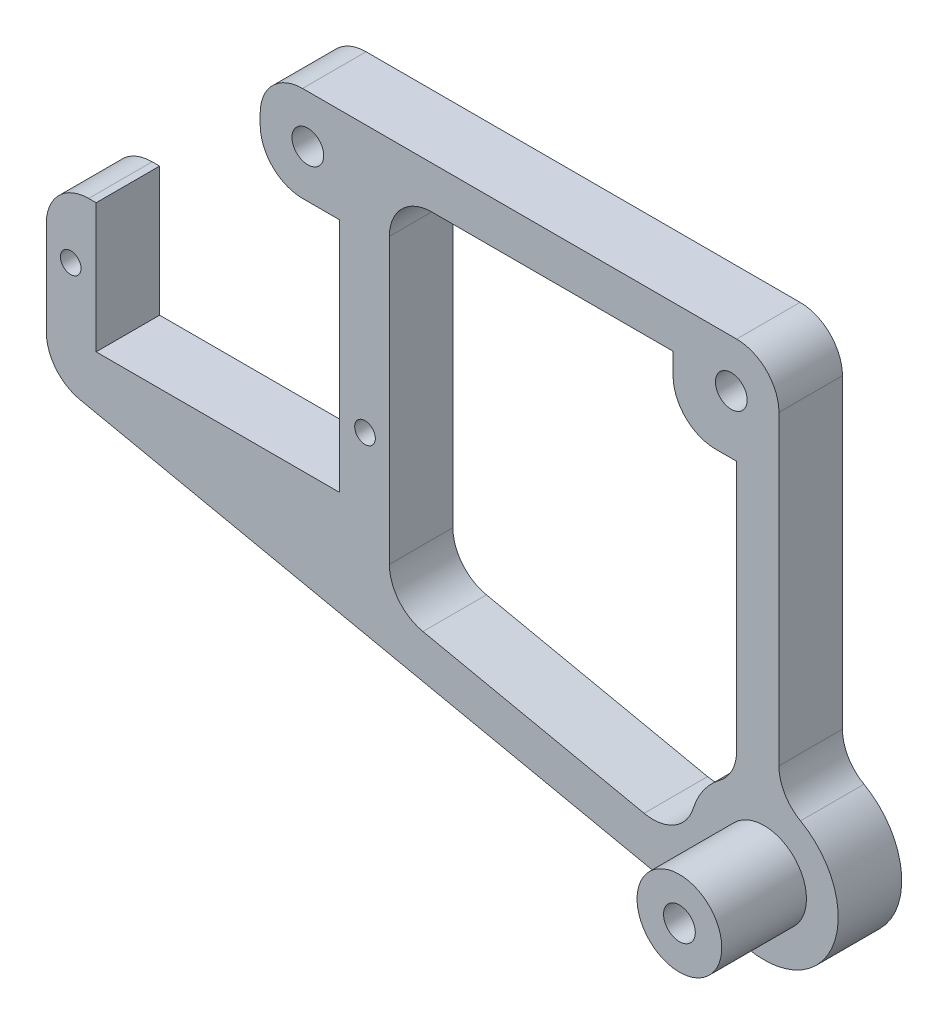
SolidWorks part; units mm, degrees
ref_plane "Front Plane" through (0, 0, 0) normal (0, 0, 1) x (1, 0, 0)
ref_plane "Top Plane" through (0, 0, 0) normal (0, 1, 0) x (1, 0, 0)
ref_plane "Right Plane" through (0, 0, 0) normal (1, 0, 0) x (0, 0, -1)
sketch "screw holes" plane through (0, 0, 0) normal (0, 0, 1) x (1, 0, 0)
  line L0 (-20, 0) -> (20, 0) construction
  circle A0 centre (-20, 0) radius 1.5
  circle A1 centre (20, 0) radius 1.5
  point P4 (0, 0)
  dimension "D1" = 3
  dimension "D2" = 40
sketch "bearings" plane through (0, 0, 0) normal (0, 0, 1) x (1, 0, 0)
  line L1 (-8, -16.5) -> (8, -16.5)
  line L2 (-8, -16.5) -> (-8, -7.5)
  line L3 (-8, -7.5) -> (8, -7.5)
  line L4 (8, -16.5) -> (8, -7.5)
  point P4 (0, -7.5)
  dimension "D1" = 7.5
  dimension "D2" = 16
  dimension "D3" = 9
sketch "bottom rod mount" plane through (0, 0, 0) normal (0, 0, 1) x (1, 0, 0)
  line L0 (-20, 0) -> (-20, -14.6) construction
  line L1 (-40, -14.6) -> (40, -14.6)
  point P6 (0, -14.6)
  dimension "D1" = 80
  dimension "D2" = 14.6
sketch "servo body" plane through (0, 0, 0) normal (0, 0, 1) x (1, 0, 0)
  line L1 (-40, -14.6) -> (-17, -14.6)
  line L2 (-40, -14.6) -> (-40, -26.8)
  line L3 (-40, -26.8) -> (-17, -26.8)
  line L4 (-17, -14.6) -> (-17, -26.8)
  line L5 (-44.7, -26.8) -> (-12.3, -26.8)
  line L6 (-44.7, -26.8) -> (-44.7, -14.6)
  line L7 (-44.7, -14.6) -> (-12.3, -14.6)
  line L8 (-12.3, -26.8) -> (-12.3, -14.6)
  point P9 (-28.5, -14.6)
  point P10 (-28.5, -14.6)
  dimension "D1" = 12.2
  dimension "D2" = 23
  dimension "D3" = 32.4
sketch "servo screw holes" plane through (0, 0, 0) normal (0, 0, 1) x (1, 0, 0)
  line L0 (-41.425, -20.7) -> (-15.575, -20.7) construction
  line L1 (-40, -26.8) -> (-17, -26.8) construction
  line L2 (-44.7, -26.8) -> (-44.7, -14.6) construction
  circle A0 centre (-42.4, -20.7) radius 0.975
  circle A1 centre (-14.6, -20.7) radius 0.975
  point P7 (-28.5, -26.8)
  point P10 (-44.7, -20.7)
  point P17 (-28.5, -20.7)
  dimension "D1" = 1.95
  dimension "D2" = 25.85
sketch "servo motor center" plane through (0, 0, 0) normal (0, 0, 1) x (1, 0, 0)
  line L0 (-40, -14.6) -> (40, -14.6) construction
  line L1 (-40, -26.8) -> (-17, -26.8) construction
  line L2 (-17, -14.6) -> (-17, -26.8) construction
  circle A0 centre (-23.1, -20.7) radius 6.1 construction
  point P9 (-23.1, -20.7)
sketch "pen pivot line" plane through (0, 0, 0) normal (0, 0, 1) x (1, 0, 0)
  line L0 (20, 0) -> (20, -38) construction
  line L1 (-34.4923, -38) -> (49965.5077, -38) construction
  dimension "D1" = 38
sketch "pen pivot point" plane through (0, 0, 0) normal (0, 0, 1) x (1, 0, 0)
  line L1 (-200034.4923, -38) -> (249965.5077, -38) construction
  circle A0 centre (23.1, -38) radius 4.6033 construction
  point P1 (-23.1, -20.7)
  point P2 (-20, 0)
  point P3 (23.1, -38)
  dimension "D1" = 3.1
  dimension "D2" = 3.1
sketch "center distance" plane through (0, 0, 0) normal (0, 0, 1) x (1, 0, 0)
  line L0 (23.1, -38) -> (-23.1, -20.7) construction
  dimension "D1" = 49.3328
sketch "body" plane through (0, 0, 0) normal (0, 0, 1) x (1, 0, 0)
  line L0 (-24.5, 4.5) -> (24.5, 4.5)
  line L6 (-24.5, -4.5) -> (-24.5, 4.5)
  line L9 (24.5, 4.5) -> (24.5, -31.1414)
  line L11 (-44.7, -14.6) -> (-40, -14.6)
  line L12 (-40, -14.6) -> (-40, -26.8)
  line L13 (-40, -26.8) -> (-17, -26.8)
  line L14 (-17, -26.8) -> (-17, -4.5)
  line L16 (-17, -4.5) -> (-24.5, -4.5)
  line L18 (-12.3, 0.5) -> (14.5, 0.5)
  line L19 (14.5, 0.5) -> (14.5, -5.5)
  line L20 (16.2912, -39.6249) -> (-12.3, -33.5713)
  line L21 (-12.3, -26.8) -> (-12.3, -14.6) construction
  line L22 (-12.3, -33.5713) -> (-12.3, 0.5)
  line L25 (14.5, -5.5) -> (20.5, -5.5)
  line L26 (20.5, -5.5) -> (20.5, -31.5008)
  line L27 (-44.7, -30.8) -> (21.65, -44.8482)
  line L28 (-44.7, -14.6) -> (-44.7, -30.8)
  circle A0 centre (-20, 0) radius 1.5 construction
  circle A1 centre (-20, 0) radius 1.5 construction
  arc A4 (20.5, -31.5008) -> (16.2912, -39.6249) centre (23.1, -38) ccw
  arc A5 (21.65, -44.8482) -> (24.5, -31.1414) centre (23.1, -38) ccw
  point P1 (-21.5, 0)
  point P16 (-20, 1.5)
  dimension "D1" = 3
  dimension "D7" = 14
  dimension "D2" = 3
  dimension "D3" = 4.5
  dimension "D5" = 4
  dimension "D6" = 4
  dimension "D8" = 4.5
  dimension "D10" = 4
  dimension "D11" = 5.5
  dimension "D12" = 5.5
  dimension "D13" = 4
extrude "Boss-Extrude1" add sketch "body" along normal blind 6
sketch "Sketch12" plane through (0, 0, 0) normal (0, 0, 1) x (1, 0, 0)
  circle A1 centre (20, 0) radius 1.5
  circle A2 centre (20, 0) radius 1.5
  circle A3 centre (-20, 0) radius 1.5
  circle A4 centre (-20, 0) radius 1.5
  dimension "D1" = 0
  dimension "D2" = 0
extrude "mount screw holes" cut sketch "Sketch12" along normal up to next
sketch "Sketch13" plane through (0, 0, 0) normal (0, 0, 1) x (1, 0, 0)
  circle A0 centre (23.1, -38) radius 4
  dimension "D1" = 8
extrude "gear shaft" add sketch "Sketch13" along normal blind 8 from surface at 6 starting at face at (21.5, 0, 6)
sketch "Sketch14" plane through (0, 0, 0) normal (0, 0, 1) x (1, 0, 0)
  circle A0 centre (23.1, -38) radius 1.5
  dimension "D1" = 3
extrude "gear screw hole" cut sketch "Sketch14" along normal through all
sketch "Sketch15" plane through (0, 0, 0) normal (0, 0, 1) x (1, 0, 0)
  circle A0 centre (-14.6, -20.7) radius 0.975 construction
  circle A1 centre (-42.4, -20.7) radius 0.975 construction
  circle A2 centre (-14.6, -20.7) radius 0.975
  circle A3 centre (-42.4, -20.7) radius 0.975
extrude "servo screw cutout" cut sketch "Sketch15" along normal through all
fillet "Fillet1" radius 4 11 edges at (-12.3, 0.5, 3) (24.5, -31.1414, 3) (-24.5, 4.5, 3) (-24.5, -4.5, 3) (24.5, 4.5, 3) (14.5, -5.5, 3) (20.5, -31.5008, 3) (16.2912, -39.6249, 3) (-12.3, -33.5713, 3) (-44.7, -30.8, 3) (-44.7, -14.6, 3)
sketch "gear sizes" plane through (0, 0, 0) normal (0, 0, 1) x (1, 0, 0)
  circle A1 centre (23.1, -38) radius 32.8886
  circle A2 centre (-23.1, -20.7) radius 16.4443
  point P7 (-23.1, -20.7)
  point P8 (-48.5542, -0.807)
  dimension "D1" = 65.7771
sketch "Sketch17" plane through (0, 0, 0) normal (0, 0, 1) x (1, 0, 0)
  circle A2 centre (-23.1, -20.7) radius 16.4443
ref_point "power axel"
equation "\"D2@pen pivot point\" = \"D1@pen pivot point\""
equation "\"D1@gear sizes\"=\"D1@center distance\" * 2 *  ( 2 / 3 )"
